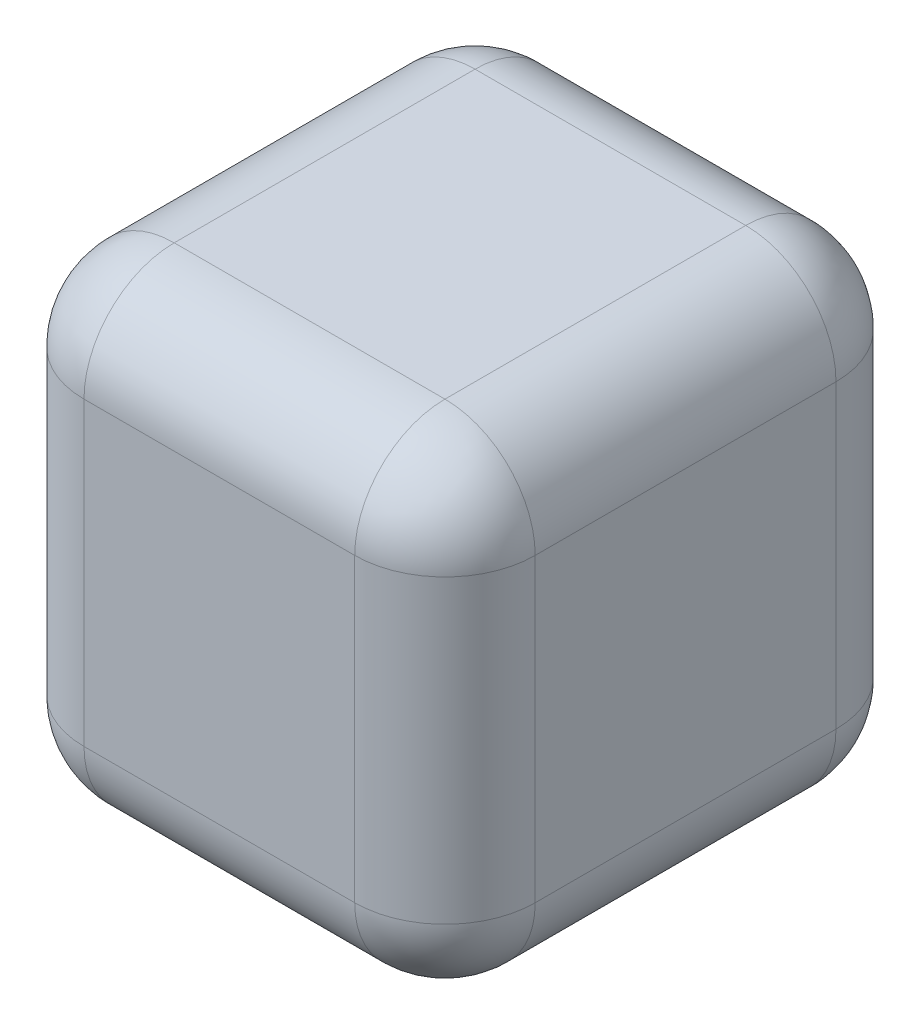
SolidWorks part; units mm, degrees
material "ABS"
ref_plane "Front Plane" through (0, 0, 0) normal (0, 0, 1) x (1, 0, 0)
ref_plane "Top Plane" through (0, 0, 0) normal (0, 1, 0) x (1, 0, 0)
ref_plane "Right Plane" through (0, 0, 0) normal (1, 0, 0) x (0, 0, -1)
ref_plane "X_WEB" through (24, 0, 0) normal (1, 0, 0) x (0, 0, -1)
sketch "Sketch1" plane through (24, 0, 0) normal (1, 0, 0) x (0, 0, -1)
  line L1 (-16, -16) -> (16, -16)
  line L2 (-16, -16) -> (-16, 16)
  line L3 (-16, 16) -> (16, 16)
  line L4 (16, -16) -> (16, 16)
extrude "Boss-Extrude1" add sketch "Sketch1" along normal blind 30
fillet "Fillet1" radius 6 12 edges at (24, 0, 16) (24, -16, 0) (24, 0, -16) (24, 16, 0) (54, 0, 16) (54, -16, 0) (54, 0, -16) (54, 16, 0) (39, 16, 16) (39, 16, -16) (39, -16, -16) (39, -16, 16)
ref_plane "X+21_20" through (21.2, 0, 0) normal (1, 0, 0) x (0, 0, -1)
sketch "Sketch2" plane through (21.2, 0, 0) normal (1, 0, 0) x (0, 0, -1)
  circle A0 centre (-4, -4) radius 1.5
  circle A1 centre (4, -4) radius 1.5
  circle A2 centre (-4, 4) radius 1.5
  circle A3 centre (4, 4) radius 1.5
extrude "Boss-Extrude2" add sketch "Sketch2" along normal blind 2.8
